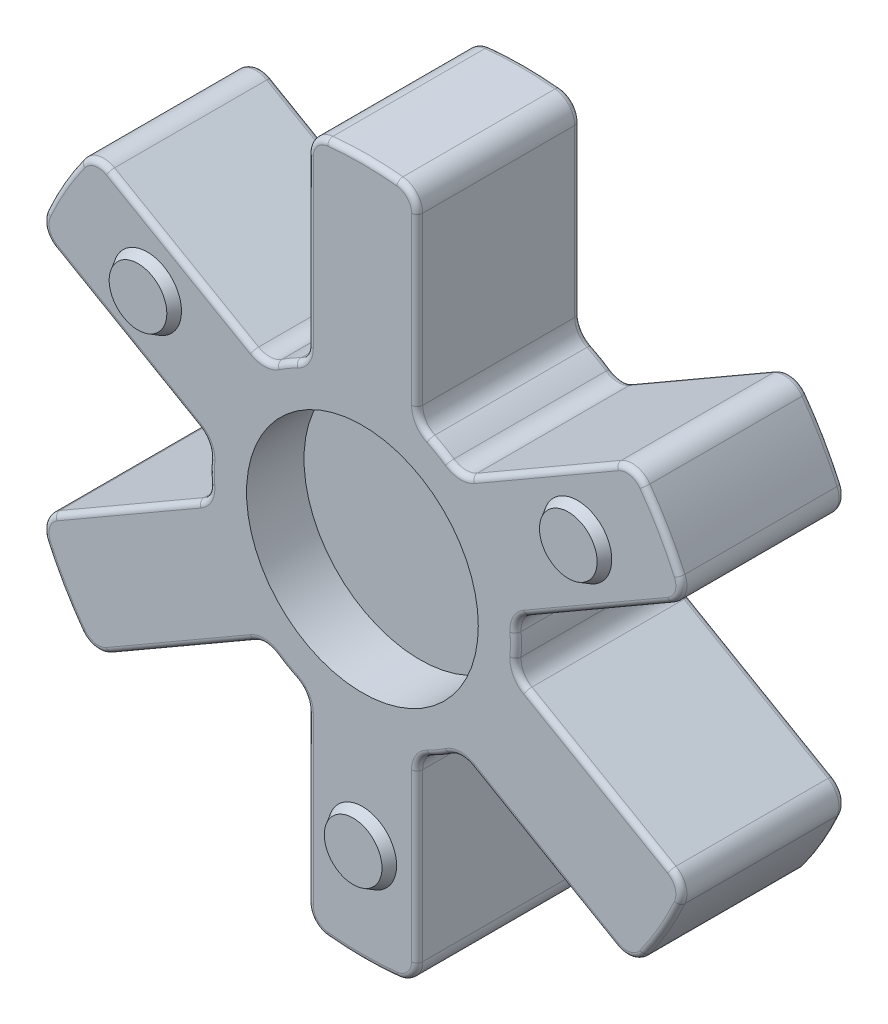
SolidWorks part; units mm, degrees
ref_plane "Front Plane" through (0, 0, 0) normal (0, 0, 1) x (1, 0, 0)
ref_plane "Top Plane" through (0, 0, 0) normal (0, 1, 0) x (1, 0, 0)
ref_plane "Right Plane" through (0, 0, 0) normal (1, 0, 0) x (0, 0, -1)
sketch "Sketch1" plane through (0, 0, 0) normal (0, 0, 1) x (1, 0, 0)
  line L0 (0, 47.0319) -> (0, 21.0344) construction
  line L1 (0, 21.0344) -> (0, 15.875) construction
  line L2 (0, 15.875) -> (0, 0) construction
  line L3 (-7.493, 47.0319) -> (7.493, 47.0319) construction
  line L4 (0, 0) -> (-41.2445, 23.8125) construction
  line L6 (41.2445, 23.8125) -> (0, 0) construction
  line L7 (0, -47.625) -> (0, 0)
  line L9 (-7.493, 47.0319) -> (-7.493, 19.6545) construction
  line L10 (7.493, 47.0319) -> (7.493, 19.6545) construction
  circle A0 centre (0, 0) radius 47.625 construction
  circle A1 centre (0, 0) radius 21.0344 construction
  circle A2 centre (0, 0) radius 15.875 construction
  circle A3 centre (-29.4735, 17.0166) radius 4.6831 construction
  circle A4 centre (29.4735, 17.0166) radius 4.6831 construction
  circle A5 centre (0, -34.0331) radius 4.6831 construction
  circle A6 centre (0, 0) radius 34.0331 construction
  point P5 (0, 34.0331)
  dimension "OD A" = 95.25
  dimension "ID H" = 31.75
  dimension "D3" = 9.3662
  dimension "D1" = 42.0688
  dimension "Arm Width B" = 14.986
  dimension "D2" = 120
sketch "Sketch2" plane through (0, 0, 0) normal (1, 0, 0) x (0, 0, -1)
  line L0 (-11.176, 15.875) -> (-3.302, 15.875)
  line L1 (-11.176, -47.625) -> (11.176, -47.625) construction
  line L2 (-11.176, -47.625) -> (-11.176, 47.625) construction
  line L3 (-11.176, 47.625) -> (11.176, 47.625) construction
  line L4 (11.176, -47.625) -> (11.176, 47.625) construction
  line L5 (0, 47.625) -> (0, -47.625) construction
  line L6 (-11.176, 0) -> (11.176, 0) construction
  line L7 (-3.302, 15.875) -> (-3.302, -15.875)
  line L8 (-3.302, -15.875) -> (-11.176, -15.875)
  line L9 (11.176, 15.875) -> (3.302, 15.875)
  line L10 (3.302, 15.875) -> (3.302, -15.875)
  line L11 (3.302, -15.875) -> (11.176, -15.875)
  point P0 (-3.302, 0)
  dimension "Width W" = 22.352
  dimension "Center Offset DD" = 7.874
sketch "Sketch3" plane through (0, 0, 0) normal (0, 0, 1) x (1, 0, 0)
  line L0 (-7.493, 47.0319) -> (-7.493, 19.6545)
  line L1 (7.493, 47.0319) -> (7.493, 19.6545) construction
  line L2 (7.493, 47.0319) -> (7.493, 19.6545)
  line L3 (0, 0) -> (-10.5172, 18.2163)
  line L4 (10.5172, 18.2163) -> (0, 0)
  line L6 (-10.5172, 18.2163) -> (10.5172, 18.2163) construction
  circle A0 centre (0, 0) radius 47.625 construction
  arc A1 (7.493, 47.0319) -> (-7.493, 47.0319) centre (0, 0) ccw
  circle A2 centre (0, 0) radius 21.0344 construction
  arc A3 (-7.493, 19.6545) -> (-10.5172, 18.2163) centre (0, 0) ccw
  arc A4 (10.5172, 18.2163) -> (7.493, 19.6545) centre (0, 0) ccw
  dimension "D1" = 60
extrude "Boss-Extrude1" add sketch "Sketch3" along normal up to vertex (11.176 mm away) up to point (0, 0, 11.176)
pattern_circular "CirPattern1" count 6 over 360 about axis through (0, 0, 0) along (0, 0, 1) of bodies 104
combine bodies "Combine1" bodies to combine 105 104 109 108 107 106
sketch "Sketch4" plane through (0, 0, 11.176) normal (0, 0, 1) x (1, 0, 0)
  circle A3 centre (-29.4735, 17.0166) radius 4.6831 construction
  circle A4 centre (0, -34.0331) radius 4.6831 construction
  circle A5 centre (29.4735, 17.0166) radius 4.6831 construction
  circle A6 centre (-29.4735, 17.0166) radius 4.6831
  circle A7 centre (0, -34.0331) radius 4.6831
  circle A8 centre (29.4735, 17.0166) radius 4.6831
extrude "Boss-Extrude2" add sketch "Sketch4" along normal offset from surface 1.27 draft 30
fillet "Fillet3" radius 2.9972 24 edges at (-36.9843, 30.0051, 5.588) (-13.2748, 16.3164, 5.588) (-20.7678, 3.3381, 5.588) (-44.4773, 17.0268, 5.588) (7.493, 47.0319, 5.588) (-7.493, 47.0319, 5.588) (-7.493, 19.6545, 5.588) (13.2748, 16.3164, 5.588) (7.493, 19.6545, 5.588) (44.4773, 17.0268, 5.588) (36.9843, 30.0051, 5.588) (20.7678, -3.3381, 5.588) (20.7678, 3.3381, 5.588) (36.9843, -30.0051, 5.588) (44.4773, -17.0268, 5.588) (7.493, -19.6545, 5.588) (13.2748, -16.3164, 5.588) (-7.493, -47.0319, 5.588) (7.493, -47.0319, 5.588) (-13.2748, -16.3164, 5.588) (-7.493, -19.6545, 5.588) (-44.4773, -17.0268, 5.588) (-36.9843, -30.0051, 5.588) (-20.7678, -3.3381, 5.588)
sketch "Sketch5" plane through (0, 0, 11.176) normal (0, 0, 1) x (1, 0, 0)
  circle A0 centre (0, 0) radius 15.875
  circle A1 centre (0, 0) radius 15.875 construction
extrude "Cut-Extrude1" cut sketch "Sketch5" against normal up to vertex (7.874 mm away) up to point (0, 0, 3.302)
mirror "Mirror1" about plane through (0, 0, 0) normal (0, 0, 1) of bodies 113 111
fillet "Fillet2" radius 0.762 96 edges at (7.493, 33.0109, 11.176) (-41.2445, 23.8125, 11.176) (-32.3348, 10.0163, 11.176) (-21.0344, 0, 11.176) (-32.3348, -10.0163, 11.176) (-41.2445, -23.8125, 11.176) (-24.8418, -22.9946, 11.176) (-10.5172, -18.2163, 11.176) (-7.493, -33.0109, 11.176) (0, -47.625, 11.176) (7.493, -33.0109, 11.176) (10.5172, -18.2163, 11.176) (24.8418, -22.9946, 11.176) (41.2445, -23.8125, 11.176) (32.3348, -10.0163, 11.176) (21.0344, 0, 11.176) (32.3348, 10.0163, 11.176) (41.2445, 23.8125, 11.176) (24.8418, 22.9946, 11.176) (10.5172, 18.2163, 11.176) (-43.5524, 17.3862, 11.176) (-36.833, 29.0244, 11.176) (36.833, 29.0244, 11.176) (43.5524, 17.3862, 11.176) (43.5524, -17.3862, 11.176) (36.833, -29.0244, 11.176) (6.7193, -46.4105, 11.176) (-6.7193, -46.4105, 11.176) (-36.833, -29.0244, 11.176) (-43.5524, -17.3862, 11.176) (-6.7193, 46.4105, 11.176) (6.7193, 46.4105, 11.176) (-13.3716, 16.9001, 11.176) (-7.9501, 20.0302, 11.176) (7.9501, 20.0302, 11.176) (13.3716, 16.9001, 11.176) (-21.3217, -3.1301, 11.176) (-13.3716, -16.9001, 11.176) (-7.9501, -20.0302, 11.176) (7.9501, -20.0302, 11.176) (13.3716, -16.9001, 11.176) (21.3217, -3.1301, 11.176) (21.3217, 3.1301, 11.176) (-21.3217, 3.1301, 11.176) (-41.2445, 23.8125, -11.176) (-32.3348, 10.0163, -11.176) (-21.0344, 0, -11.176) (-10.5172, 18.2163, -11.176) (-24.8418, 22.9946, -11.176) (0, 47.625, -11.176) (-7.493, 33.0109, -11.176) (10.5172, 18.2163, -11.176) (7.493, 33.0109, -11.176) (41.2445, 23.8125, -11.176) (24.8418, 22.9946, -11.176) (21.0344, 0, -11.176) (32.3348, 10.0163, -11.176) (41.2445, -23.8125, -11.176) (32.3348, -10.0163, -11.176) (10.5172, -18.2163, -11.176) (24.8418, -22.9946, -11.176) (0, -47.625, -11.176) (7.493, -33.0109, -11.176) (-10.5172, -18.2163, -11.176) (-7.493, -33.0109, -11.176) (-41.2445, -23.8125, -11.176) (-24.8418, -22.9946, -11.176) (-32.3348, -10.0163, -11.176) (-13.3716, 16.9001, -11.176) (-7.9501, 20.0302, -11.176) (6.7193, 46.4105, -11.176) (7.9501, 20.0302, -11.176) (13.3716, 16.9001, -11.176) (-6.7193, 46.4105, -11.176) (-43.5524, -17.3862, -11.176) (-21.3217, -3.1301, -11.176) (-13.3716, -16.9001, -11.176) (-36.833, -29.0244, -11.176) (-6.7193, -46.4105, -11.176) (-7.9501, -20.0302, -11.176) (7.9501, -20.0302, -11.176) (6.7193, -46.4105, -11.176) (36.833, -29.0244, -11.176) (13.3716, -16.9001, -11.176) (21.3217, -3.1301, -11.176) (43.5524, -17.3862, -11.176) (43.5524, 17.3862, -11.176) (21.3217, 3.1301, -11.176) (36.833, 29.0244, -11.176) (-36.833, 29.0244, -11.176) (-21.3217, 3.1301, -11.176) (-43.5524, 17.3862, -11.176) (-24.8418, 22.9946, 11.176) (-10.5172, 18.2163, 11.176) (-7.493, 33.0109, 11.176) (0, 47.625, 11.176)
equation "\"D3@Sketch1\"=\"Arm Width B@Sketch1\"*.625"
equation "\"D1@Sketch1\"=\"ID H@Sketch1\"*1.325"
equation "\"D1@Fillet3\"=\"Arm Width B@Sketch1\"*.2"
